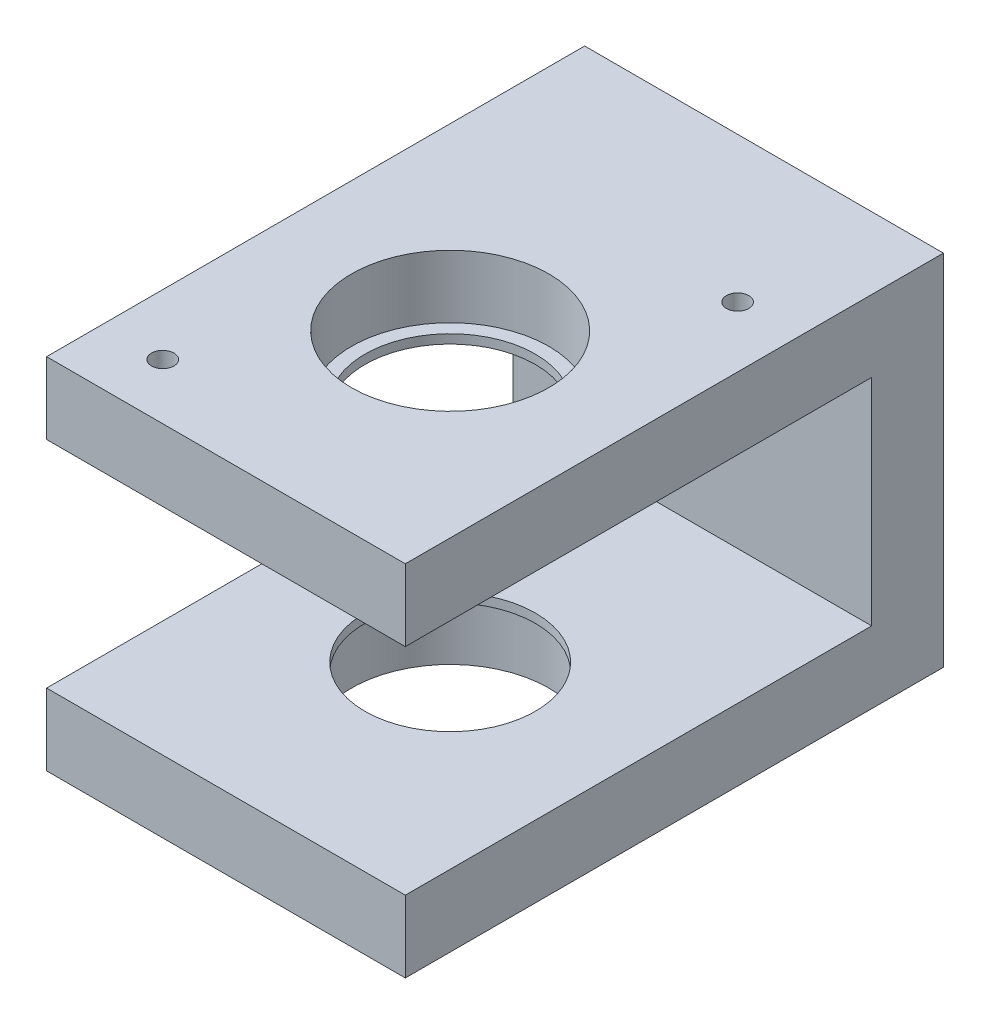
SolidWorks part; units mm, degrees
material "5052-H32"
ref_plane "Front Plane" through (0, 0, 0) normal (0, 0, 1) x (1, 0, 0)
ref_plane "Top Plane" through (0, 0, 0) normal (0, 1, 0) x (1, 0, 0)
ref_plane "Right Plane" through (0, 0, 0) normal (1, 0, 0) x (0, 0, -1)
ref_plane "Plane1" through (0, 40, 0) normal (0, 1, 0) x (1, 0, 0)
sketch "Sketch1" plane through (0, 40, 0) normal (0, 1, 0) x (1, 0, 0)
  line L0 (0, 0) -> (0, -60)
  line L1 (0, -60) -> (40, -60)
  line L2 (40, -60) -> (40, 0)
  line L3 (40, 0) -> (0, 0)
  dimension "D1" = 40
  dimension "D2" = 60
extrude "Boss-Extrude1" add sketch "Sketch1" against normal blind 40
sketch "Sketch2" plane through (40, 0, 0) normal (1, 0, 0) x (0, 0, -1)
  line L0 (-60, 32) -> (-60, 8)
  line L1 (-60, 8) -> (-8, 8)
  line L2 (-8, 8) -> (-8, 32)
  line L3 (-8, 32) -> (-60, 32)
  line L4 (-60, 0) -> (0, 0) construction
  line L5 (-60, 40) -> (0, 40) construction
  line L6 (0, 0) -> (0, 40) construction
  dimension "D1" = 8
  dimension "D2" = 8
  dimension "D3" = 8
extrude "Cut-Extrude1" cut sketch "Sketch2" against normal through all
hole_wizard "Ø4.5 (4.5) Diameter Hole1" positions "Sketch4" profile "Sketch3" hole size "Ø4.5" standard "ANSI Metric" end condition through all
sketch "Sketch4" plane through (0, 0, 8) normal (0, 0, 1) x (1, 0, 0)
  point P0 (20, 20)
sketch "Sketch3" plane through (20, 20, 8) normal (1, 0, 0) x (0, -1, 0)
  line L0 (0, 0) -> (0, 8)
  line L1 (0, 8) -> (2.25, 8)
  line L2 (2.25, 8) -> (2.25, 0)
  line L5 (2.25, 0) -> (0, 0)
  line L11 (0, -6.35) -> (0, 107.95) construction
  dimension "Thru Hole Dia." = 4.5
  dimension "Thru Hole Depth" = 8
hole_wizard "Ø22.0 (22) Diameter Hole2" positions "Sketch6" profile "Sketch5" hole size "Ø22.0" standard "ANSI Metric"
sketch "Sketch6" plane through (0, 40, 0) normal (0, -1, 0) x (-1, 0, 0)
  point P0 (-20, -35)
sketch "Sketch5" plane through (20, 40, 35) normal (1, 0, 0) x (0, 0, 1)
  line L0 (0, 0) -> (0, 7)
  line L1 (0, 7) -> (11, 7)
  line L2 (11, 7) -> (11, 0)
  line L5 (11, 0) -> (0, 0)
  line L10 (0, 7) -> (-11, 7) construction
  line L11 (0, -6.35) -> (0, 107.95) construction
  dimension "Hole Dia." = 22
  dimension "Hole Depth" = 7
  dimension "Drill Angle" = 180
hole_wizard "Ø22.0 (22) Diameter Hole1" positions "Sketch8" profile "Sketch7" hole size "Ø22.0" standard "ANSI Metric"
sketch "Sketch8" plane through (0, 0, 0) normal (0, 1, 0) x (1, 0, 0)
  point P0 (20, -35)
sketch "Sketch7" plane through (20, 0, 35) normal (1, 0, 0) x (0, 0, -1)
  line L0 (0, 0) -> (0, 7)
  line L1 (0, 7) -> (11, 7)
  line L2 (11, 7) -> (11, 0)
  line L5 (11, 0) -> (0, 0)
  line L10 (0, 7) -> (-11, 7) construction
  line L11 (0, -6.35) -> (0, 107.95) construction
  dimension "Hole Dia." = 22
  dimension "Hole Depth" = 7
  dimension "Drill Angle" = 180
hole_wizard "Ø2.5 (2.5) Diameter Hole1" positions "Sketch10" profile "Sketch9" hole size "Ø2.5" standard "ANSI Metric"
sketch "Sketch10" plane through (0, 40, 0) normal (0, 1, 0) x (1, 0, 0)
  point P0 (33.2499, -16.2)
  point P1 (6.7501, -53.8)
sketch "Sketch9" plane through (33.2499, 40, 16.2) normal (1, 0, 0) x (0, 0, 1)
  line L0 (0, 0) -> (0, 8.7217)
  line L1 (0, 8.7217) -> (1.25, 8)
  line L2 (1.25, 8) -> (1.25, 0)
  line L5 (1.25, 0) -> (0, 0)
  line L10 (0, 8.7217) -> (-1.25, 8) construction
  line L11 (0, -6.35) -> (0, 107.95) construction
  dimension "Hole Dia." = 2.5
  dimension "Hole Depth" = 8
  dimension "Drill Angle" = 120
chamfer "Chamfer1" distance 2 angle 45 1 edges at (22.25, 20, 8)
hole_wizard "Ø19.0 (19) Diameter Hole1" positions "Sketch12" profile "Sketch11" hole size "Ø19.0" standard "ANSI Metric" end condition through all
sketch "Sketch12" plane through (0, 7, 0) normal (0, -1, 0) x (-1, 0, 0)
  point P0 (-20, -35)
sketch "Sketch11" plane through (20, 7, 35) normal (1, 0, 0) x (0, 0, -1)
  line L0 (0, 0) -> (0, 33)
  line L1 (0, 33) -> (9.5, 33)
  line L2 (9.5, 33) -> (9.5, 0)
  line L5 (9.5, 0) -> (0, 0)
  line L11 (0, -6.35) -> (0, 107.95) construction
  dimension "Thru Hole Dia." = 19
  dimension "Thru Hole Depth" = 33
sketch "Sketch13" plane through (0, 0, 8) normal (0, 0, 1) x (1, 0, 0)
  line L0 (20, 20) -> (0, 20) construction
  line L2 (0, 8) -> (0, 32) construction
  circle A0 centre (10, 20) radius 1
  dimension "D1" = 2
  dimension "D2" = 10
extrude "2mm Pin" cut sketch "Sketch13" against normal up to next
